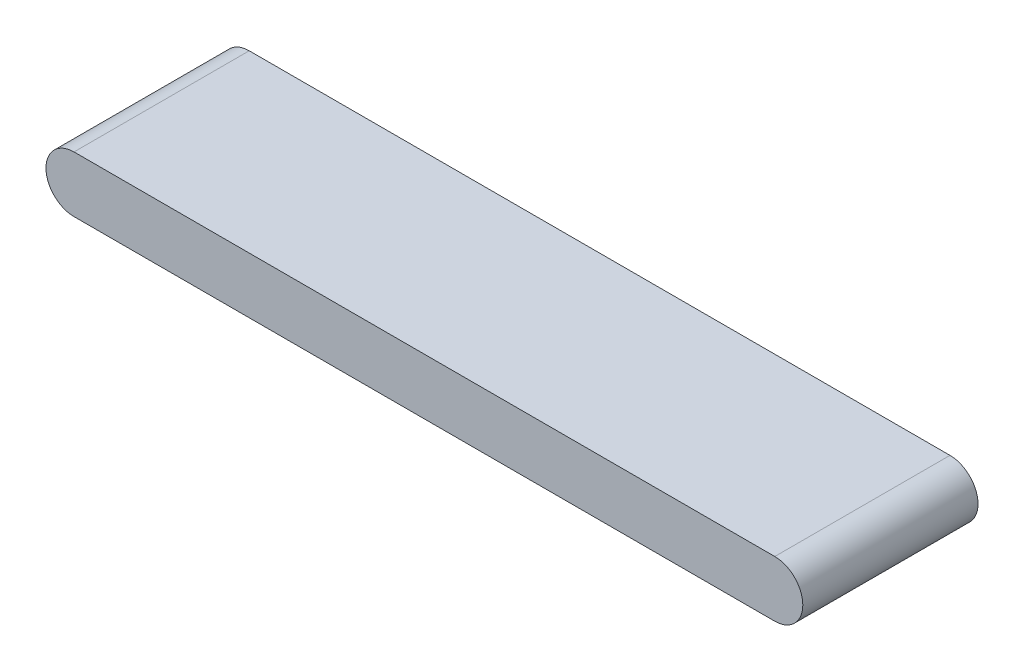
SolidWorks part; units mm, degrees
ref_plane "Front Plane" through (0, 0, 0) normal (0, 0, 1) x (1, 0, 0)
ref_plane "Top Plane" through (0, 0, 0) normal (0, 1, 0) x (1, 0, 0)
ref_plane "Right Plane" through (0, 0, 0) normal (1, 0, 0) x (0, 0, -1)
sketch "Sketch1" plane through (0, 0, 0) normal (0, 0, 1) x (1, 0, 0)
  line L0 (-1000, 0) -> (1000, 0) construction
  line L1 (-1000, 80) -> (1000, 80)
  line L2 (-1000, -80) -> (1000, -80)
  arc A0 (-1000, 80) -> (-1000, -80) centre (-1000, 0) ccw
  arc A1 (1000, -80) -> (1000, 80) centre (1000, 0) ccw
  point P2 (0, 0)
  dimension "D2" = 80
  dimension "D1" = 2000
extrude "Boss-Extrude1" add sketch "Sketch1" along normal mid plane 500
